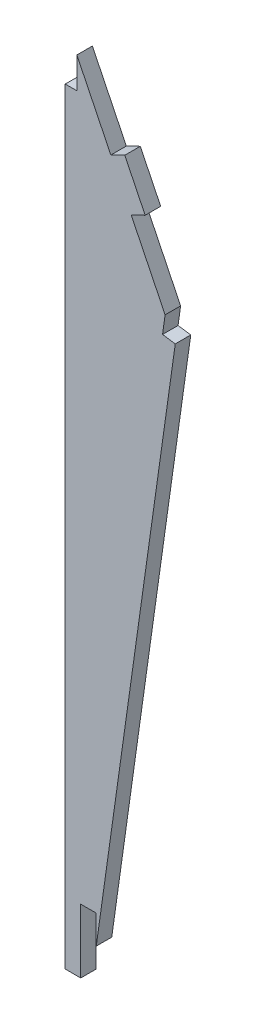
SolidWorks part; units mm, degrees
ref_plane "前视基准面" through (0, 0, 0) normal (0, 0, 1) x (1, 0, 0)
ref_plane "上视基准面" through (0, 0, 0) normal (0, 1, 0) x (1, 0, 0)
ref_plane "右视基准面" through (0, 0, 0) normal (1, 0, 0) x (0, 0, -1)
sketch "草图1" plane through (0, 0, 0) normal (0, 0, 1) x (1, 0, 0)
  line L0 (11.1121, 105.7016) -> (11.1121, 101.7016)
  line L1 (11.1121, 101.7016) -> (9.6121, 101.7016)
  line L2 (9.6121, 101.7016) -> (9.6121, 2.8316)
  line L3 (9.6121, 2.8316) -> (11.6121, 2.8316)
  line L4 (11.6121, 2.8316) -> (11.6121, 11.0816)
  line L5 (11.6121, 11.0816) -> (13.6121, 11.0816)
  line L6 (13.6121, 11.0816) -> (13.6121, 7.3907)
  line L7 (13.6121, 7.3907) -> (23.806, 79.7711)
  line L8 (23.806, 79.7711) -> (22.1644, 80.0023)
  line L9 (22.1644, 80.0023) -> (22.4965, 82.3602)
  line L10 (11.1121, 105.7016) -> (15.4958, 96.7136)
  line L11 (15.4958, 96.7136) -> (17.2934, 97.5904)
  line L12 (17.2934, 97.5904) -> (19.9237, 92.1976)
  line L13 (19.9237, 92.1976) -> (18.1261, 91.3209)
  line L14 (18.1261, 91.3209) -> (22.4965, 82.3602)
extrude "凸台-拉伸1" add sketch "草图1" along normal blind 2
